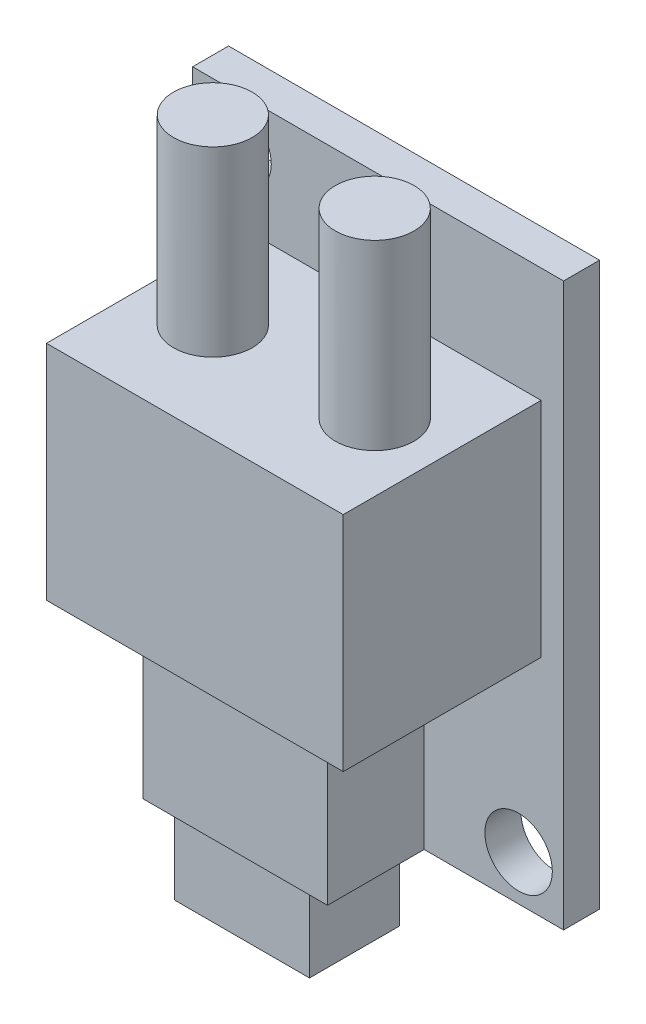
SolidWorks part; units mm, degrees
ref_plane "Ebene vorne" through (0, 0, 0) normal (0, 0, 1) x (1, 0, 0)
ref_plane "Ebene oben" through (0, 0, 0) normal (0, 1, 0) x (1, 0, 0)
ref_plane "Ebene rechts" through (0, 0, 0) normal (1, 0, 0) x (0, 0, -1)
sketch "Sketch1" plane through (0, 0, 0) normal (0, 0, 1) x (1, 0, 0)
  line L0 (8.25, 0) -> (-8.25, 0) construction
  line L1 (-8.25, -12.5) -> (8.25, -12.5)
  line L2 (-8.25, -12.5) -> (-8.25, 12.5)
  line L3 (-8.25, 12.5) -> (8.25, 12.5)
  line L4 (8.25, -12.5) -> (8.25, 12.5)
  line L5 (0, -12.5) -> (0, 12.5) construction
  point P9 (0, 0)
  dimension "D1" = 16.5
  dimension "D2" = 25
extrude "Boss-Extrude1" add sketch "Sketch1" along normal blind 1.6
sketch "Sketch2" plane through (0, 0, 1.6) normal (0, 0, 1) x (1, 0, 0)
  line L0 (8.25, 12.5) -> (-8.25, 12.5) construction
  line L1 (8.25, -12.5) -> (8.25, 12.5) construction
  line L2 (-8.25, 12.5) -> (-8.25, -12.5) construction
  line L3 (-8.25, -12.5) -> (8.25, -12.5) construction
  circle A0 centre (-6.25, 10.5) radius 1.5
  circle A1 centre (6.25, -10.5) radius 1.5
  dimension "D1" = 3
  dimension "D2" = 2
  dimension "D5" = 2
  dimension "D3" = 2
  dimension "D4" = 2
extrude "Cut-Extrude1" cut sketch "Sketch2" against normal through all
sketch "Sketch3" plane through (0, 0, 1.6) normal (0, 0, 1) x (1, 0, 0)
  line L0 (0, -12.5) -> (0, 12.5) construction
  line L1 (-5.95, 7.4) -> (7.25, 7.4)
  line L2 (-5.95, 7.4) -> (-5.95, -2.5)
  line L3 (-5.95, -2.5) -> (7.25, -2.5)
  line L4 (7.25, 7.4) -> (7.25, -2.5)
  line L5 (-8.25, -12.5) -> (8.25, -12.5) construction
  line L6 (8.25, 12.5) -> (-8.25, 12.5) construction
  line L7 (8.25, -12.5) -> (8.25, 12.5) construction
  dimension "D1" = 9.9
  dimension "D2" = 13.2
  dimension "D3" = 1
  dimension "D4" = 10
extrude "Boss-Extrude2" add sketch "Sketch3" along normal blind 8.8
sketch "Sketch4" plane through (0, 7.4, 0) normal (0, 1, 0) x (1, 0, 0)
  line L0 (-5.95, -10.4) -> (-5.95, -1.6) construction
  line L1 (7.25, -10.4) -> (7.25, -1.6) construction
  line L2 (-5.95, -6) -> (7.25, -6) construction
  circle A0 centre (-2.95, -6) radius 1.75
  circle A1 centre (4.25, -6) radius 1.75
  dimension "D1" = 3.5
  dimension "D2" = 3
  dimension "D3" = 3
extrude "Boss-Extrude3" add sketch "Sketch4" along normal blind 8.1
sketch "Sketch5" plane through (0, 0, 1.6) normal (0, 0, 1) x (1, 0, 0)
  line L0 (-8.25, -12.5) -> (8.25, -12.5) construction
  line L1 (-6.15, -6.8976) -> (2.05, -6.8976)
  line L2 (-6.15, -6.8976) -> (-6.15, -12.5)
  line L3 (-6.15, -12.5) -> (2.05, -12.5)
  line L4 (2.05, -6.8976) -> (2.05, -12.5)
  line L5 (-8.25, 12.5) -> (-8.25, -12.5) construction
  dimension "D1" = 2.1
  dimension "D2" = 8.2
extrude "Boss-Extrude4" add sketch "Sketch5" along normal blind 4.3
sketch "Sketch6" plane through (0, -12.5, 0) normal (0, -1, 0) x (-1, 0, 0)
  line L0 (8.25, -1.6) -> (6.15, -1.6) construction
  line L1 (5.05, -5.6) -> (-0.95, -5.6)
  line L2 (5.05, -5.6) -> (5.05, -1.6)
  line L3 (5.05, -1.6) -> (-0.95, -1.6)
  line L4 (-0.95, -5.6) -> (-0.95, -1.6)
  line L5 (2.05, -5.9) -> (2.05, 0.7266) construction
  line L6 (6.15, -5.9) -> (-2.05, -5.9) construction
  dimension "D1" = 6
  dimension "D2" = 4
extrude "Boss-Extrude5" add sketch "Sketch6" along normal blind 3.5
